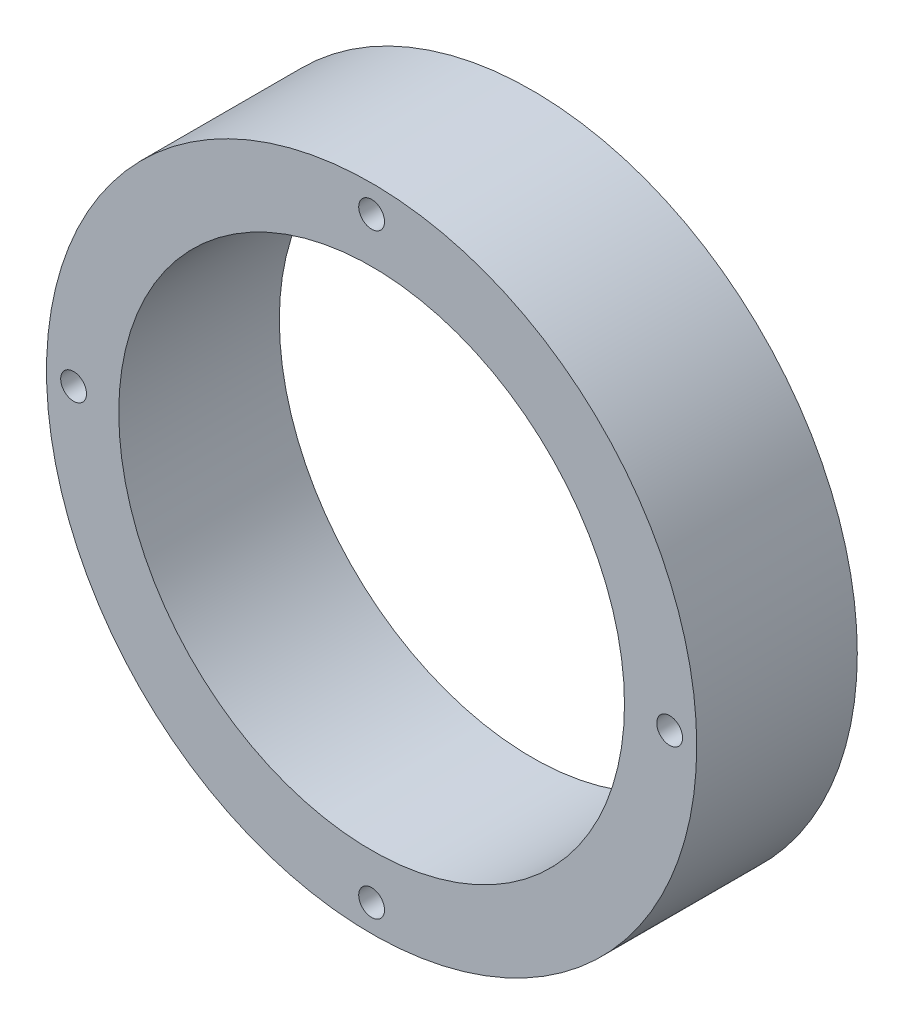
SolidWorks part; units mm, degrees
ref_plane "Front Plane" through (0, 0, 0) normal (0, 0, 1) x (1, 0, 0)
ref_plane "Top Plane" through (0, 0, 0) normal (0, 1, 0) x (1, 0, 0)
ref_plane "Right Plane" through (0, 0, 0) normal (1, 0, 0) x (0, 0, -1)
sketch "Sketch1" plane through (0, 0, 0) normal (0, 0, 1) x (1, 0, 0)
  circle A0 centre (0, 0) radius 45
  circle A1 centre (0, 0) radius 35
  circle A2 centre (0, 0) radius 41.25 construction
  circle A3 centre (0, 41.25) radius 1.7859
  circle A4 centre (41.25, 0) radius 1.7859
  circle A5 centre (0, -41.25) radius 1.7859
  circle A6 centre (-41.25, 0) radius 1.7859
  point P16 (0, 0)
  dimension "D1" = 90
  dimension "D2" = 70
  dimension "D3" = 82.5
  dimension "D4" = 3.5719
  dimension "D5" = 4
extrude "Boss-Extrude1" add sketch "Sketch1" along normal blind 22.225
sketch "Sketch2" plane through (0, 0, 0) normal (0, 0, -1) x (-1, 0, 0)
  line L0 (15.7154, -15.7154) -> (0, 0) construction
  line L1 (0, 0) -> (0, -22.225) construction
  circle A0 centre (0, 0) radius 35
  circle A2 centre (0, 0) radius 22.225 construction
  circle A3 centre (15.7154, -15.7154) radius 1.7859
  circle A4 centre (-15.7154, -15.7154) radius 1.7859
  circle A5 centre (-15.7154, 15.7154) radius 1.7859
  circle A6 centre (15.7154, 15.7154) radius 1.7859
  circle A7 centre (0, 0) radius 19.05
  point P15 (0, 0)
  dimension "D1" = 70
  dimension "D2" = 44.45
  dimension "D3" = 3.5719
  dimension "D5" = 38.1
  dimension "D6" = 45
  dimension "D4" = 4
extrude "Boss-Extrude2" [suppressed] add sketch "Sketch2" against normal blind 6.35
